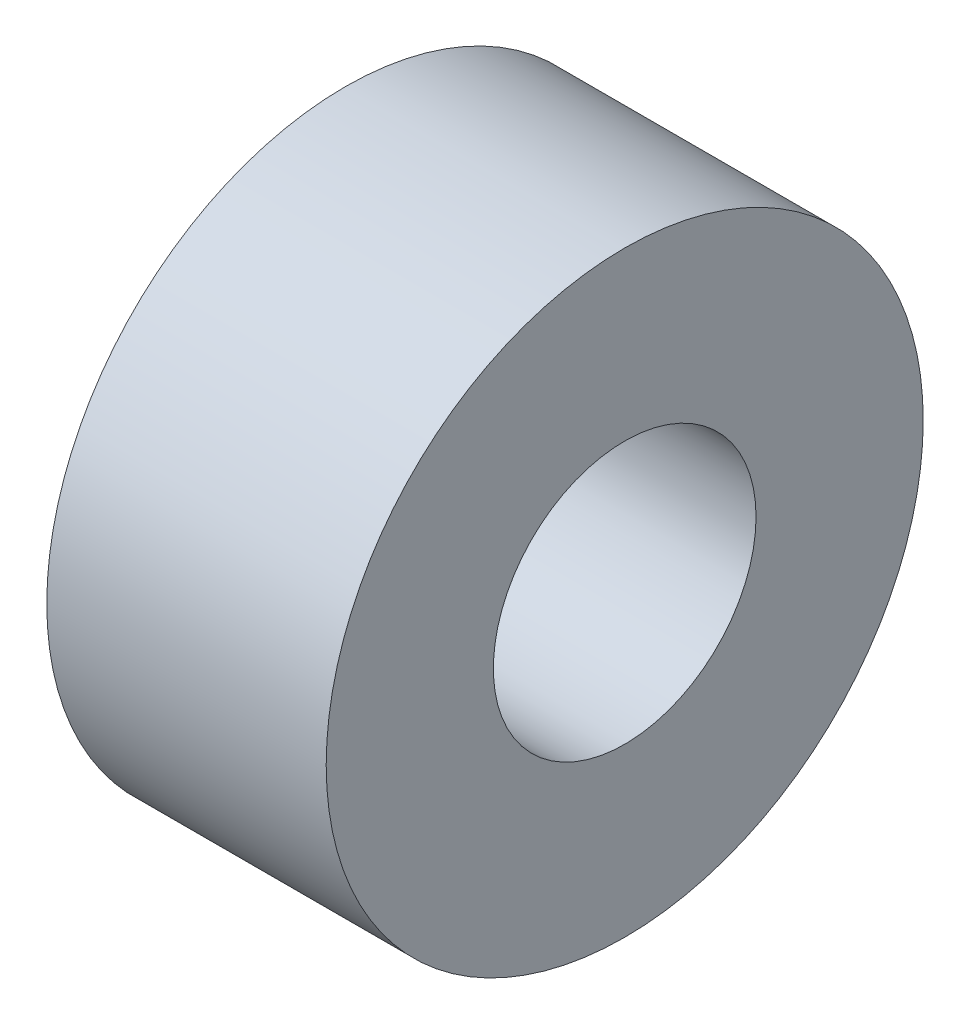
SolidWorks part; units mm, degrees
ref_plane "Front Plane" through (0, 0, 0) normal (1, 0, 0) x (0, 1, 0)
ref_plane "Top Plane" through (0, 0, 0) normal (0, 0, 1) x (0, 1, 0)
ref_plane "Right Plane" through (0, 0, 0) normal (0, 1, 0) x (-1, 0, 0)
sketch "Sketch1" plane through (0, 0, 0) normal (1, 0, 0) x (0, 1, 0)
  circle A0 centre (0, 0) radius 3.175
  circle A1 centre (0, 0) radius 1.397
  dimension "D1" = 2.794
  dimension "D2" = 6.35
extrude "Boss-Extrude1" add sketch "Sketch1" along normal blind 2.9718
